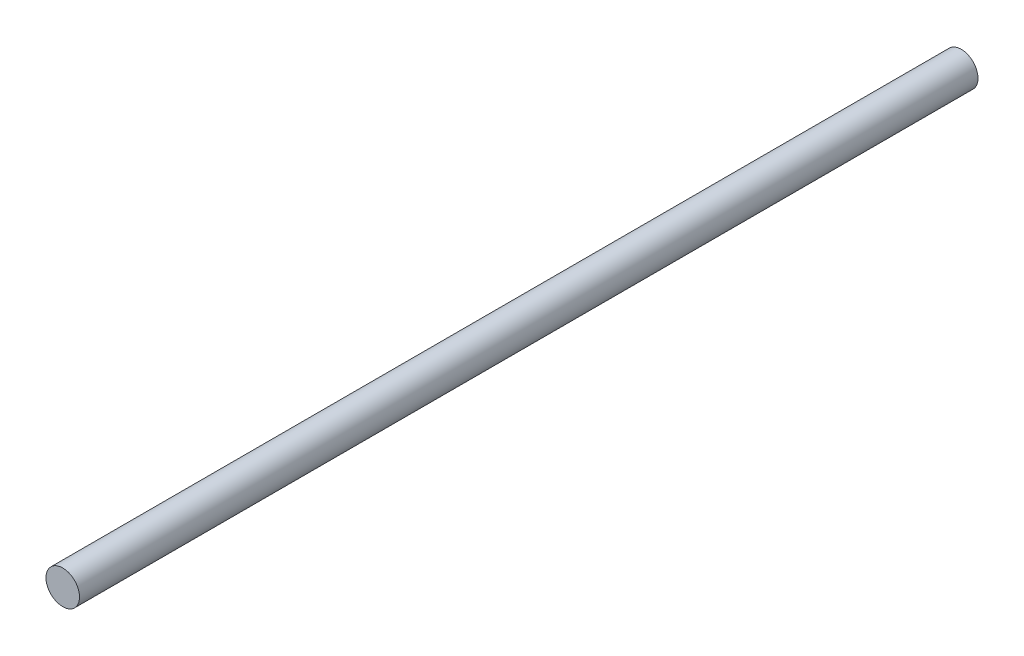
SolidWorks part; units mm, degrees
ref_plane "Front Plane" through (0, 0, 0) normal (0, 0, 1) x (1, 0, 0)
ref_plane "Top Plane" through (0, 0, 0) normal (0, 1, 0) x (1, 0, 0)
ref_plane "Right Plane" through (0, 0, 0) normal (1, 0, 0) x (0, 0, -1)
sketch "Sketch1" plane through (0, 0, 0) normal (0, 0, 1) x (1, 0, 0)
  circle A0 centre (0, 0) radius 0.7937
  dimension "D1" = 1.5875
extrude "Boss-Extrude1" add sketch "Sketch1" along normal blind 42.5
